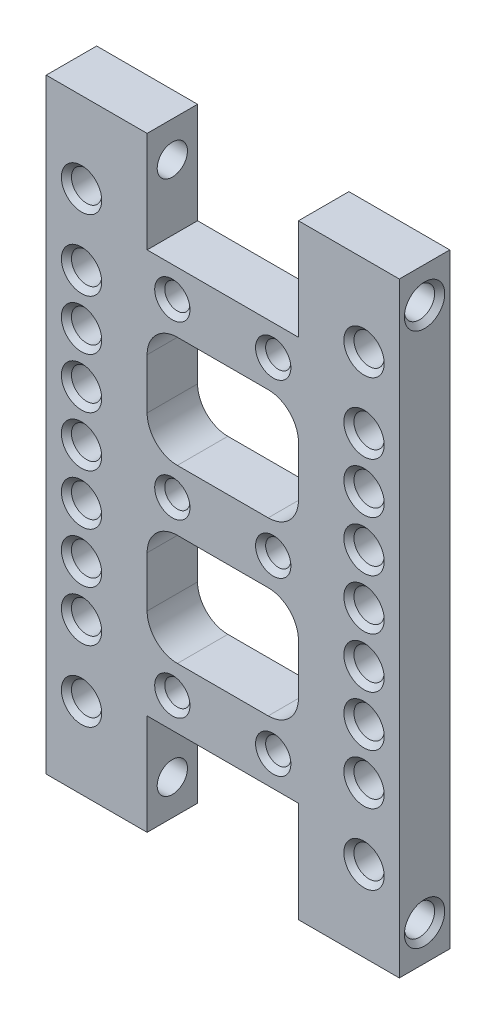
SolidWorks part; units mm, degrees
material "6063-O"
ref_plane "前视基准面" through (0, 0, 0) normal (0, 0, 1) x (1, 0, 0)
ref_plane "上视基准面" through (0, 0, 0) normal (0, 1, 0) x (1, 0, 0)
ref_plane "右视基准面" through (0, 0, 0) normal (1, 0, 0) x (0, 0, -1)
other "质心 (COM)"
sketch "草图1" plane through (0, 0, 0) normal (0, 0, 1) x (1, 0, 0)
  line L1 (-17.5, -30) -> (17.5, -30)
  line L2 (-17.5, -30) -> (-17.5, 30)
  line L3 (-17.5, 30) -> (17.5, 30)
  line L4 (17.5, -30) -> (17.5, 30)
  line L5 (-17.5, -30) -> (17.5, 30) construction
  line L6 (-17.5, 30) -> (17.5, -30) construction
  point P0 (0, 0)
  dimension "D1" = 60
  dimension "D2" = 35
extrude "凸台-拉伸1" add sketch "草图1" along normal blind 5
sketch "草图2" plane through (0, 0, 5) normal (0, 0, 1) x (1, 0, 0)
  line L0 (0, 30) -> (0, -30) construction
  line L1 (17.5, 30) -> (-17.5, 30) construction
  line L2 (-17.5, -30) -> (17.5, -30) construction
  line L3 (-23.1473, 0) -> (22.9425, 0) construction
  line L4 (7.5, 20) -> (-7.5, 20)
  line L5 (7.5, 20) -> (7.5, 30)
  line L6 (7.5, 30) -> (-7.5, 30)
  line L7 (-7.5, 20) -> (-7.5, 30)
  line L8 (7.5, 20) -> (-7.5, 30) construction
  line L9 (7.5, 30) -> (-7.5, 20) construction
  line L10 (7.5, -30) -> (-7.5, -20) construction
  line L11 (7.5, -20) -> (-7.5, -30) construction
  line L12 (-7.5, -20) -> (-7.5, -30)
  line L13 (7.5, -30) -> (-7.5, -30)
  line L14 (7.5, -20) -> (7.5, -30)
  line L15 (7.5, -20) -> (-7.5, -20)
  line L16 (-14, 30) -> (-14, -30) construction
  line L17 (14, 30) -> (14, -30) construction
  line L18 (-7.5, 3) -> (7.5, 14) construction
  line L19 (-7.5, 14) -> (7.5, 3) construction
  line L20 (7.5, 11) -> (7.5, 6)
  line L21 (-4.5, 3) -> (4.5, 3)
  line L22 (-7.5, 11) -> (-7.5, 6)
  line L23 (-4.5, 14) -> (4.5, 14)
  line L24 (-5, 17) -> (5, 17) construction
  line L25 (-4.5, -14) -> (4.5, -14)
  line L26 (-7.5, -11) -> (-7.5, -6)
  line L27 (-4.5, -3) -> (4.5, -3)
  line L28 (7.5, -11) -> (7.5, -6)
  line L29 (-7.5, -14) -> (7.5, -3) construction
  line L30 (-7.5, -3) -> (7.5, -14) construction
  circle A0 centre (-14, 0) radius 1.5
  circle A1 centre (-14, -15) radius 1.5
  circle A2 centre (14, -15) radius 1.5
  circle A3 centre (14, 0) radius 1.5
  circle A4 centre (-14, -10) radius 1.5
  circle A5 centre (-14, -22) radius 1.5
  circle A6 centre (14, -22) radius 1.5
  circle A7 centre (14, -10) radius 1.5
  circle A8 centre (-14, 22) radius 1.5
  circle A9 centre (14, 22) radius 1.5
  circle A10 centre (14, 10) radius 1.5
  circle A11 centre (-14, 10) radius 1.5
  circle A12 centre (14, 15) radius 1.5
  circle A13 centre (-14, 15) radius 1.5
  arc A14 (7.5, -6) -> (4.5, -3) centre (4.5, -6) ccw
  arc A15 (7.5, -11) -> (4.5, -14) centre (4.5, -11) cw
  arc A16 (-4.5, -14) -> (-7.5, -11) centre (-4.5, -11) cw
  arc A17 (-7.5, -6) -> (-4.5, -3) centre (-4.5, -6) cw
  arc A18 (-7.5, 6) -> (-4.5, 3) centre (-4.5, 6) ccw
  arc A19 (-4.5, 14) -> (-7.5, 11) centre (-4.5, 11) ccw
  arc A20 (7.5, 11) -> (4.5, 14) centre (4.5, 11) ccw
  arc A21 (7.5, 6) -> (4.5, 3) centre (4.5, 6) cw
  circle A22 centre (-5, 0) radius 0.5
  circle A23 centre (5, 0) radius 0.5
  circle A24 centre (-14, -5) radius 1.5
  circle A25 centre (14, -5) radius 1.5
  circle A26 centre (14, 5) radius 1.5
  circle A27 centre (-14, 5) radius 1.5
  circle A28 centre (-5, 17) radius 0.5
  circle A29 centre (5, 17) radius 0.5
  circle A30 centre (5, -17) radius 0.5
  circle A31 centre (-5, -17) radius 0.5
  point P6 (0, 25)
  point P18 (0, -25)
  point P56 (0, -8.5)
  point P84 (0, 8.5)
  dimension "D5" = 3
  dimension "D6" = 15
  dimension "D7" = 8
  dimension "D8" = 10
  dimension "D12" = 3
  dimension "D13" = 10
  dimension "D14" = 5
  dimension "D15" = 10
  dimension "D17" = 5
  dimension "D18" = 5
  dimension "D19" = 1
  dimension "D1" = 10
  dimension "D2" = 15
  dimension "D3" = 14
  dimension "D4" = 14
  dimension "D9" = 3
  dimension "D10" = 6
  dimension "D11" = 15
  dimension "D16" = 3
extrude "切除-拉伸1" cut sketch "草图2" against normal through all
sketch "草图3" plane through (17.5, 0, 0) normal (1, 0, 0) x (0, 0, -1)
  line L0 (-2.5, 30) -> (-2.5, -30) construction
  line L1 (-5, 30) -> (0, 30) construction
  line L2 (-5, -30) -> (0, -30) construction
  circle A0 centre (-2.5, -26.5) radius 1.5
  circle A1 centre (-2.5, 26.5) radius 1.5
  dimension "D1" = 3
  dimension "D2" = 3.5
  dimension "D3" = 3.5
extrude "切除-拉伸2" cut sketch "草图3" against normal through all
hole_wizard "M3 螺纹孔1" positions "草图5" profile "草图4" tap size "M3" standard "GB" end condition through all
sketch "草图5" plane through (0, 0, 5) normal (0, 0, 1) x (1, 0, 0)
  point P1 (-5, 17)
  point P4 (5, 17)
  point P7 (-5, 0)
  point P10 (5, 0)
  point P13 (-5, -17)
  point P16 (5, -17)
sketch "草图4" plane through (-5, 17, 5) normal (1, 0, 0) x (0, -1, 0)
  line L0 (0, 0) -> (0, 5)
  line L1 (0, 5) -> (1.25, 5)
  line L2 (1.25, 5) -> (1.25, 0)
  line L5 (1.25, 0) -> (0, 0)
  line L11 (0, -6.35) -> (0, 107.95) construction
  dimension "通孔螺纹孔钻头直径" = 2.5
  dimension "通孔螺纹孔钻头深度" = 5
cosmetic thread "孔螺蚊线1" parameters "D2"=3
cosmetic thread "孔螺蚊线2" parameters "D2"=3
cosmetic thread "孔螺蚊线3" parameters "D2"=3
cosmetic thread "孔螺蚊线4" parameters "D2"=3
cosmetic thread "孔螺蚊线5" parameters "D2"=3
cosmetic thread "孔螺蚊线6" parameters "D2"=3
chamfer "倒角1" distance 0.5 angle 45 52 edges at (12.5, 0, 5) (15.5, 5, 5) (15.5, 10, 5) (15.5, 15, 5) (15.5, 22, 5) (12.5, -5, 5) (12.5, -10, 5) (12.5, -15, 5) (12.5, -22, 5) (-12.5, -22, 5) (-12.5, -15, 5) (-12.5, -10, 5) (-12.5, -5, 5) (-12.5, 0, 5) (-15.5, 5, 5) (-15.5, 10, 5) (-15.5, 15, 5) (-15.5, 22, 5) (-15.5, 15, 0) (-15.5, 10, 0) (-15.5, 5, 0) (-12.5, 0, 0) (-12.5, -5, 0) (-12.5, -15, 0) (-12.5, -22, 0) (12.5, -22, 0) (12.5, -15, 0) (12.5, -10, 0) (12.5, -5, 0) (12.5, 0, 0) (15.5, 5, 0) (15.5, 10, 0) (15.5, 15, 0) (-15.5, 22, 0) (15.5, 22, 0) (-3.75, -17, 0) (6.25, -17, 0) (-3.75, 0, 0) (6.25, 0, 0) (-3.75, 17, 0) (6.25, 17, 0) (6.25, 17, 5) (-3.75, 17, 5) (6.25, 0, 5) (-3.75, 0, 5) (6.25, -17, 5) (-3.75, -17, 5) (-12.5, -10, 0) (17.5, -26.5, 1) (-17.5, -26.5, 1) (-17.5, 26.5, 1) (17.5, 26.5, 1)
